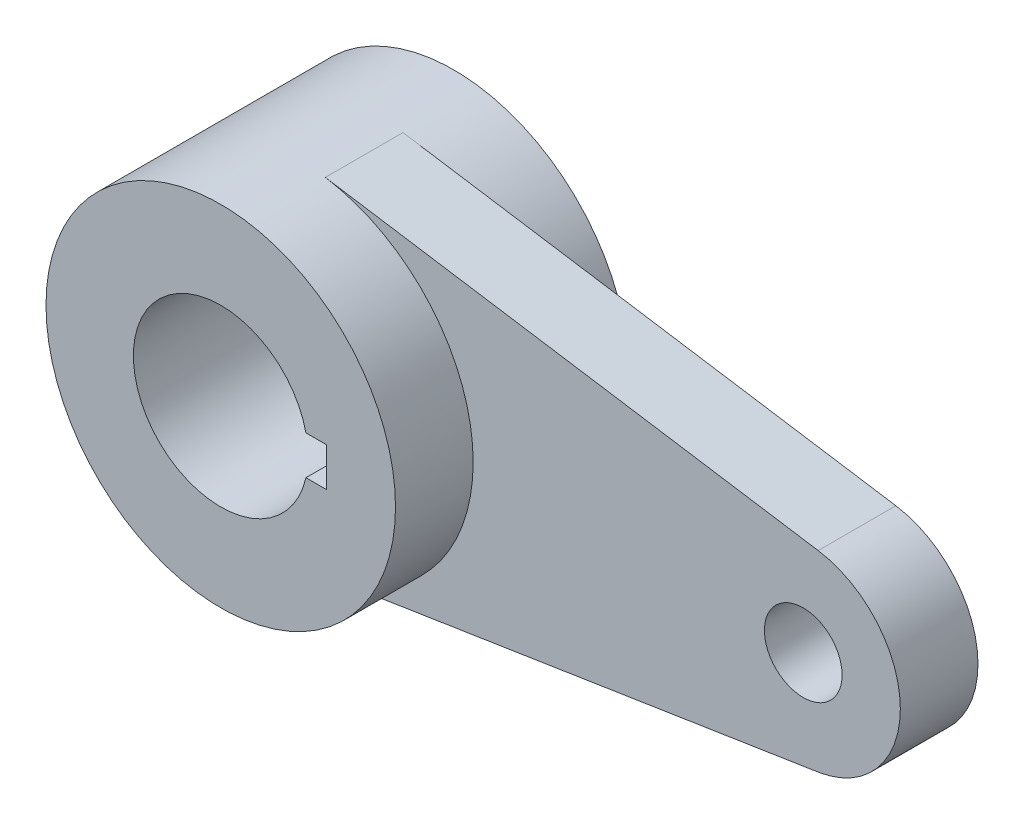
SolidWorks part; units mm, degrees
material "6061 Alloy"
ref_plane "Front Plane" through (0, 0, 0) normal (0, 0, 1) x (1, 0, 0)
ref_plane "Top Plane" through (0, 0, 0) normal (0, 1, 0) x (1, 0, 0)
ref_plane "Right Plane" through (0, 0, 0) normal (1, 0, 0) x (0, 0, -1)
sketch "Sketch2" plane through (0, 0, 0) normal (0, 0, 1) x (1, 0, 0)
  line L0 (-0.0318, 0.1364) -> (82.5182, 0.1364) construction
  line L1 (4.3644, 28.3712) -> (84.9605, 15.8224) construction
  line L2 (13.8985, -3.0386) -> (17.2402, -3.0386) construction
  line L3 (13.8985, -3.0386) -> (13.8985, 3.3114) construction
  line L4 (13.8985, 3.3114) -> (17.2402, 3.3114) construction
  line L5 (17.2402, -3.0386) -> (17.2402, 3.3114) construction
  line L6 (13.8985, -3.0386) -> (17.2402, 3.3114) construction
  line L7 (13.8985, 3.3114) -> (17.2402, -3.0386) construction
  line L11 (4.3644, -28.0984) -> (84.9605, -15.5496) construction
  circle A2 centre (-0.0318, 0.1364) radius 14.2875
  circle A4 centre (-0.0318, 0.1364) radius 28.575
  circle A5 centre (82.5182, 0.1364) radius 6.35 construction
  circle A6 centre (82.5182, 0.1364) radius 15.875 construction
  point P14 (0, 0)
  dimension "D1" = 82.55
  dimension "D3" = 31.75
  dimension "D5" = 57.15
  dimension "D6" = 6.35
  dimension "D7" = 17.272
  dimension "D2" = 12.7
  dimension "D4" = 28.575
extrude "Boss-Extrude1" add sketch "Sketch2" along normal mid plane 38.1
sketch "Sketch5" plane through (0, 0, 0) normal (0, 0, 1) x (1, 0, 0)
  line L0 (4.3644, 28.3712) -> (84.9605, 15.8224)
  line L1 (84.9605, -15.5496) -> (4.3644, -28.0984)
  arc A0 (84.9605, 15.8224) -> (84.9605, -15.5496) centre (82.5182, 0.1364) cw
  arc A1 (4.3644, -28.0984) -> (4.3644, 28.3712) centre (-0.0318, 0.1364) ccw
extrude "Boss-Extrude3" add sketch "Sketch5" along normal mid plane 12.7
sketch "Sketch6" plane through (0, 0, 0) normal (0, 0, 1) x (1, 0, 0)
  line L0 (13.8985, -3.0386) -> (17.2402, 3.3114) construction
  line L1 (17.2402, -3.0386) -> (13.8985, -3.0386)
  line L2 (17.2402, -3.0386) -> (17.2402, 3.3114)
  line L3 (17.2402, 3.3114) -> (13.8985, 3.3114)
  line L4 (13.8985, -3.0386) -> (13.8985, 3.3114)
  line L5 (17.2402, -3.0386) -> (13.8985, 3.3114) construction
  line L6 (17.2402, 3.3114) -> (13.8985, -3.0386) construction
  circle A0 centre (82.5182, 0.1364) radius 6.35
  point P0 (15.5693, 0.1364)
  dimension "D1" = 12.7
extrude "Cut-Extrude3" cut sketch "Sketch6" against normal through all both and the other way through all
